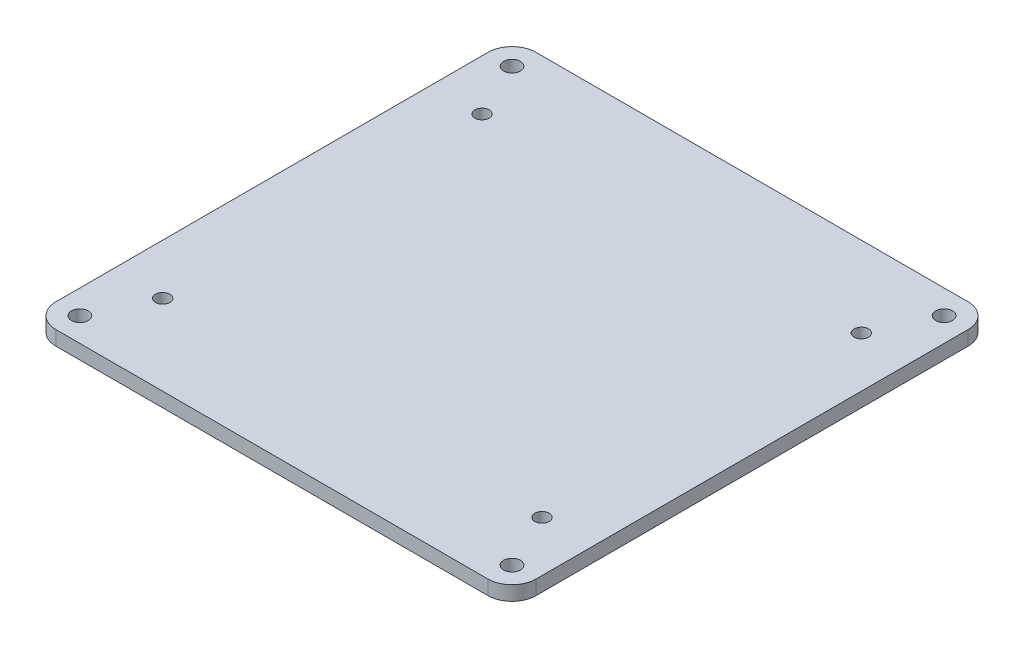
SolidWorks part; units mm, degrees
material "普通碳钢"
ref_plane "前视基准面" through (0, 0, 0) normal (0, 0, 1) x (1, 0, 0)
ref_plane "上视基准面" through (0, 0, 0) normal (0, 1, 0) x (1, 0, 0)
ref_plane "右视基准面" through (0, 0, 0) normal (1, 0, 0) x (0, 0, -1)
sketch "草图1" plane through (0, 0, 0) normal (0, 1, 0) x (1, 0, 0)
  line L1 (-45, 50) -> (45, 50)
  line L2 (-50, 45) -> (-50, -45)
  line L3 (-45, -50) -> (45, -50)
  line L4 (50, 45) -> (50, -45)
  line L5 (-50, 50) -> (50, -50) construction
  line L6 (-50, -50) -> (50, 50) construction
  arc A0 (50, -45) -> (45, -50) centre (45, -45) cw
  arc A1 (-45, -50) -> (-50, -45) centre (-45, -45) cw
  arc A2 (45, 50) -> (50, 45) centre (45, 45) cw
  arc A3 (-50, 45) -> (-45, 50) centre (-45, 45) cw
  circle A4 centre (-45, 45) radius 1.75
  circle A5 centre (45, 45) radius 1.75
  circle A6 centre (-45, -45) radius 1.75
  circle A7 centre (45, -45) radius 1.75
  circle A20 centre (-39.5, 33.25) radius 1.5
  circle A21 centre (39.5, 33.25) radius 1.5
  circle A22 centre (-39.5, -33.25) radius 1.5
  circle A23 centre (39.5, -33.25) radius 1.5
  point P0 (0, 0)
  dimension "D2" = 5
  dimension "D3" = 100
  dimension "D19" = 79
  dimension "D1" = 100
  dimension "D20" = 66.5
  dimension "D21" = 33.25
  dimension "D22" = 39.5
extrude "凸台-拉伸1" add sketch "草图1" along normal blind 3
